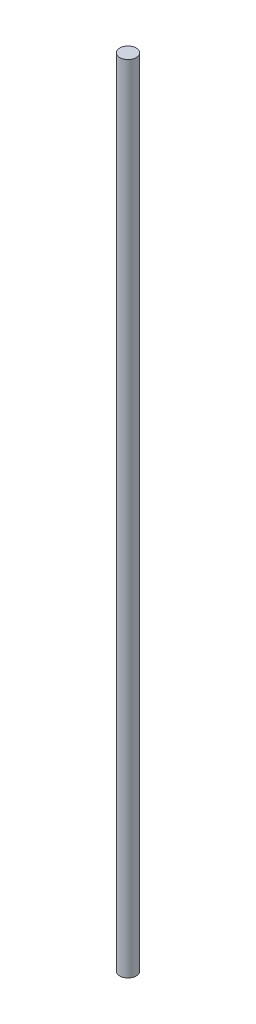
SolidWorks part; units mm, degrees
ref_plane "Front Plane" through (0, 0, 0) normal (0, 0, 1) x (1, 0, 0)
ref_plane "Top Plane" through (0, 0, 0) normal (0, 1, 0) x (1, 0, 0)
ref_plane "Right Plane" through (0, 0, 0) normal (1, 0, 0) x (0, 0, -1)
sketch "Sketch1" plane through (0, 0, 0) normal (0, 1, 0) x (1, 0, 0)
  circle A0 centre (0, 0) radius 25.4
extrude "Boss-Extrude1" add sketch "Sketch1" along normal blind 2438.4
